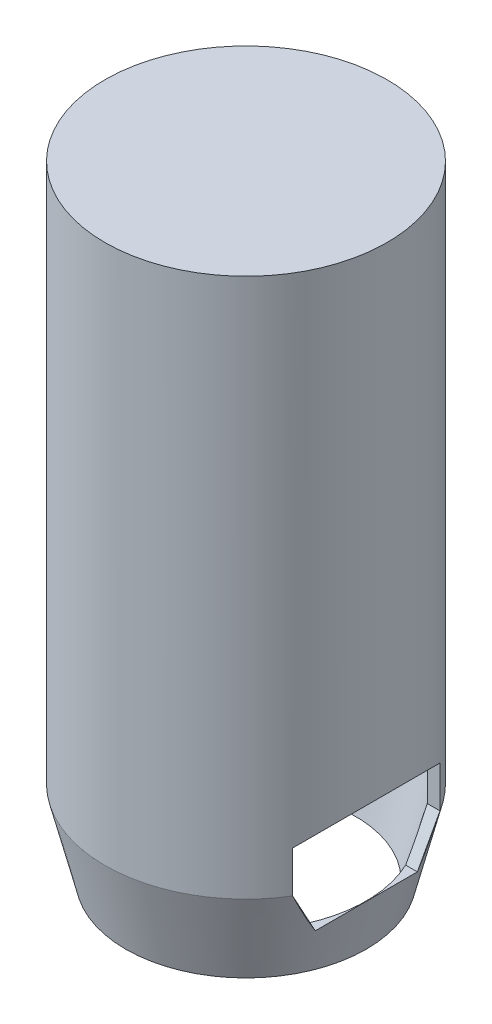
SolidWorks part; units mm, degrees
ref_plane "Front Plane" through (0, 0, 0) normal (0, 0, 1) x (1, 0, 0)
ref_plane "Top Plane" through (0, 0, 0) normal (0, 1, 0) x (1, 0, 0)
ref_plane "Right Plane" through (0, 0, 0) normal (1, 0, 0) x (0, 0, -1)
sketch "Sketch3" plane through (0, 0, 0) normal (0, 1, 0) x (1, 0, 0)
  circle A0 centre (0, 0) radius 68
  dimension "D1" = 136
extrude "Boss-Extrude1" add sketch "Sketch3" along normal blind 300
ref_axis "Axis1" through (0, 300, 0) along (0, -1, 0)
sketch "Sketch5" plane through (0, 0, 0) normal (0, 0, 1) x (1, 0, 0)
  line L1 (-68, 300) -> (-68, 0) construction
  line L3 (-68, 0) -> (68, 0) construction
  line L4 (-58, 0) -> (-68, 0)
  line L5 (-68, 0) -> (-68, 40)
  line L6 (-68, 40) -> (-58, 0)
  dimension "D1" = 40
  dimension "D2" = 10
revolve "Cut-Revolve1" cut sketch "Sketch5" angle 360 about axis through (0, 300, 0) along (0, -1, 0)
shell "Shell1" thickness 5
sketch "Sketch6" plane through (0, 0, 0) normal (0, 0, 1) x (1, 0, 0)
  line L0 (-68, 70) -> (-68, 30)
  line L1 (-68, 300) -> (-68, 40) construction
  line L2 (-68, 30) -> (-58, 20)
  line L3 (-58, 20) -> (-58, 60)
  line L4 (-58, 60) -> (-68, 70)
  line L6 (68, 40) -> (-68, 40) construction
  line L7 (0, -74.8) -> (0, 74.8) construction
  line L8 (68, 30) -> (58, 20)
  line L9 (58, 20) -> (58, 60)
  line L10 (58, 60) -> (68, 70)
  line L11 (68, 70) -> (68, 30)
  point P8 (-76.477, 27.3228)
  point P11 (-66.2393, 21.9505)
  dimension "D1" = 40
  dimension "D2" = 40
  dimension "D3" = 10
  dimension "D4" = 45
  dimension "D5" = 10
extrude "Cut-Extrude1" cut sketch "Sketch6" against normal through all both and the other way through all
sketch "Sketch7" plane through (-58, 0, 0) normal (-1, 0, 0) x (0, 0, 1)
  line L0 (-35.4965, 60) -> (35.4965, 60)
  line L1 (35.4965, 60) -> (35.4965, 40)
  line L2 (35.4965, 40) -> (24.5967, 20)
  line L3 (24.5967, 20) -> (-24.5967, 20)
  line L4 (-24.5967, 20) -> (-35.4965, 40)
  line L5 (-35.4965, 40) -> (-35.4965, 60)
extrude "Cut-Extrude2" cut sketch "Sketch7" against normal up to surface (116 mm away)
